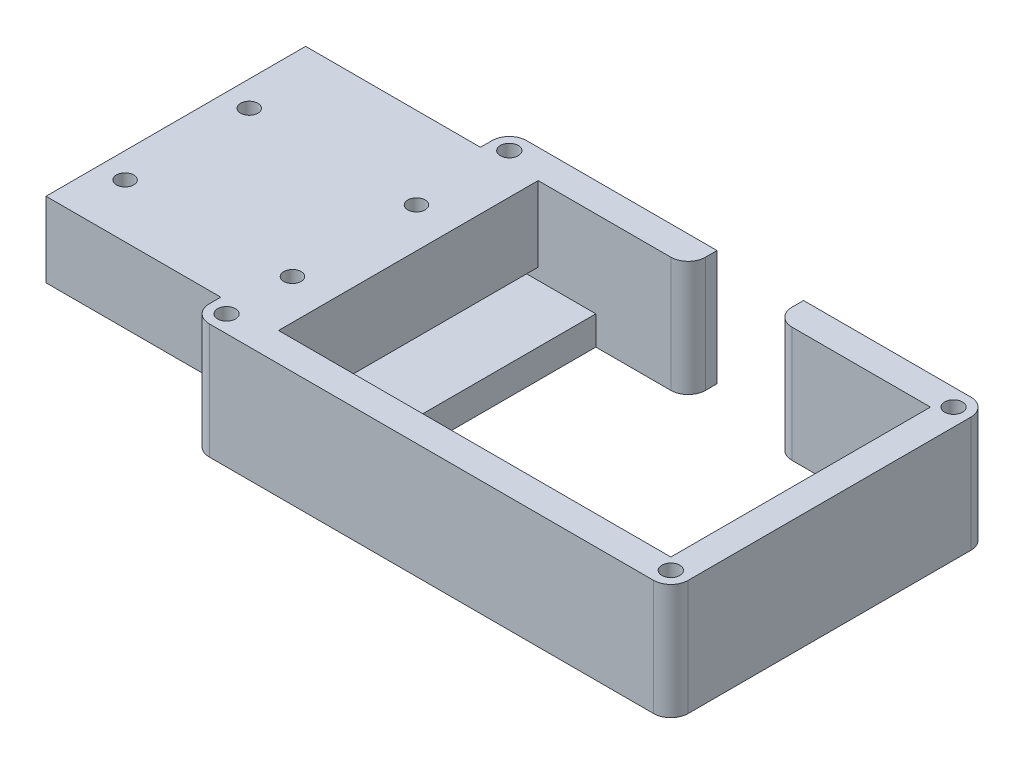
SolidWorks part; units mm, degrees
ref_plane "前视基准面" through (0, 0, 0) normal (0, 0, 1) x (1, 0, 0)
ref_plane "上视基准面" through (0, 0, 0) normal (0, 1, 0) x (1, 0, 0)
ref_plane "右视基准面" through (0, 0, 0) normal (1, 0, 0) x (0, 0, -1)
other "Configuration Table"
sketch "草图1" plane through (0, 0, 0) normal (0, 0, 1) x (1, 0, 0)
  line L0 (-1.15, 3.9875) -> (-1.15, 12)
  line L1 (0, 0) -> (0, 9.969) construction
  line L2 (-1.15, 12) -> (-4.15, 12)
  line L3 (-4.15, 12) -> (-4.15, 4.3333)
  line L4 (4.15, 12) -> (4.15, 4.3333)
  line L5 (1.15, 12) -> (4.15, 12)
  line L6 (1.15, 3.9875) -> (1.15, 12)
  line L7 (-8, -2.2655) -> (-5.2977, 2.8168)
  line L8 (-8, -2.2655) -> (-8, -30)
  line L9 (4.2426, -4.2426) -> (0, -8.4853)
  line L10 (0, -8.4853) -> (0, -30)
  line L11 (-8, -30) -> (0, -30)
  arc A0 (-1.15, 3.9875) -> (1.15, 3.9875) centre (0, 0) ccw
  arc A1 (-4.15, 4.3333) -> (-5.2977, 2.8168) centre (0, 0) ccw
  arc A2 (4.2426, -4.2426) -> (4.15, 4.3333) centre (0, 0) ccw
  dimension "D1" = 8.3
  dimension "D4" = 12
  dimension "D2" = 2.3
  dimension "D3" = 12
  dimension "D5" = 3
  dimension "D6" = 30
  dimension "D7" = 152
  dimension "D8" = 8
  dimension "D9" = 135
extrude "凸台-拉伸1" add sketch "草图1" along normal mid plane 20
sketch "草图2" plane through (0, 0, 0) normal (1, 0, 0) x (0, 0, -1)
  line L0 (-10, -30) -> (10, -30) construction
  circle A0 centre (0, -30) radius 10
extrude "凸台-拉伸2" add sketch "草图2" against normal up to surface and the other way blind 2 up to face at (-8, -16.1327, 0)
sketch "草图6" plane through (4.15, 0, 0) normal (1, 0, 0) x (0, 0, -1)
  line L0 (0, 0) -> (0, 16.5087) construction
  line L1 (-10, 12) -> (10, 12) construction
  line L2 (-5.5, 7.5) -> (-20.2045, 7.5)
  line L3 (-5.5, 7.5) -> (-5.5, 16.0204)
  line L4 (-5.5, 16.0204) -> (-20.2045, 16.0204)
  line L5 (-20.2045, 7.5) -> (-20.2045, 16.0204)
  line L6 (20.2045, 7.5) -> (20.2045, 16.0204)
  line L7 (5.5, 16.0204) -> (20.2045, 16.0204)
  line L8 (5.5, 7.5) -> (5.5, 16.0204)
  line L9 (5.5, 7.5) -> (20.2045, 7.5)
  circle A0 centre (0, 9.5) radius 1.65
  dimension "D3" = 3.3
  dimension "D1" = 11
  dimension "D2" = 4.5
  dimension "D4" = 2.5
extrude "切除-拉伸2" cut sketch "草图6" against normal through all
fillet "圆角1" radius 1 8 edges at (2.65, 7.5, -10) (-2.65, 7.5, -10) (-2.65, 7.5, 10) (2.65, 7.5, 10) (-2.65, 12, 5.5) (2.65, 12, -5.5) (-2.65, 12, -5.5) (2.65, 12, 5.5)
fillet "圆角2" radius 0.5 4 edges at (2.65, 7.5, -5.5) (-2.65, 7.5, -5.5) (2.65, 7.5, 5.5) (-2.65, 7.5, 5.5)
sketch "草图7" plane through (2, 0, 0) normal (1, 0, 0) x (0, 0, -1)
  line L0 (0, -20) -> (-22, -20)
  line L1 (0, -40) -> (-22, -40)
  line L2 (-22, -20) -> (-22, -40)
  arc A0 (0, -20) -> (0, -40) centre (0, -30) cw
  arc A1 (10, -30) -> (-10, -30) centre (0, -30) ccw construction
  dimension "D1" = 22
  dimension "D2" = 22
extrude "凸台-拉伸3" add sketch "草图7" along normal blind 8
sketch "草图8" plane through (0, 0, 22) normal (0, 0, 1) x (1, 0, 0)
  line L0 (2, -27) -> (2, -49.77) construction
  line L1 (10, -20) -> (-26, -20)
  line L2 (-26, -20) -> (-26, -40)
  line L3 (-26, -40) -> (2, -40)
  line L4 (10, -20) -> (57, -20)
  line L5 (2, -40) -> (57, -40)
  line L6 (57, -20) -> (57, -40)
  dimension "D1" = 36
  dimension "D2" = 20
  dimension "D3" = 47
extrude "凸台-拉伸4" add sketch "草图8" along normal blind 55
sketch "草图9" plane through (0, -20, 0) normal (0, 1, 0) x (1, 0, 0)
  line L0 (57, -22) -> (10, -22) construction
  line L1 (-21, -27) -> (52, -27)
  line L2 (-21, -27) -> (-21, -72)
  line L3 (-21, -72) -> (52, -72)
  line L4 (52, -27) -> (52, -72)
  line L5 (57, -77) -> (57, -22) construction
  line L6 (-26, -77) -> (-26, -22) construction
  line L7 (57, -77) -> (-26, -77) construction
  dimension "D1" = 5
  dimension "D2" = 5
  dimension "D3" = 5
  dimension "D4" = 5
extrude "切除-拉伸3" cut sketch "草图9" against normal blind 13
sketch "草图10" plane through (0, 0, 22) normal (0, 0, -1) x (-1, 0, 0)
  line L0 (-10, -40) -> (-57, -40) construction
  line L1 (-10, -20) -> (-25, -20)
  line L2 (-10, -20) -> (-10, -40)
  line L3 (-10, -40) -> (-25, -40)
  line L4 (-25, -20) -> (-25, -40)
  dimension "D1" = 15
extrude "切除-拉伸4" cut sketch "草图10" against normal blind 13
sketch "草图11" plane through (0, -33, 0) normal (0, 1, 0) x (1, 0, 0)
  line L1 (-21, -72) -> (52, -72)
  line L2 (-21, -72) -> (-21, -27)
  line L3 (-21, -27) -> (52, -27)
  line L4 (52, -72) -> (52, -27)
extrude "切除-拉伸6" cut sketch "草图11" against normal blind 13
sketch "草图12" plane through (0, -40, 0) normal (0, -1, 0) x (1, 0, 0)
  line L0 (-21, 72) -> (52, 72) construction
  line L1 (-21, 27) -> (-6, 27)
  line L2 (-21, 27) -> (-21, 72)
  line L3 (-21, 72) -> (-6, 72)
  line L4 (-6, 27) -> (-6, 72)
  line L6 (52, 27) -> (42, 27)
  line L7 (52, 27) -> (52, 72)
  line L8 (52, 72) -> (42, 72)
  line L9 (42, 27) -> (42, 72)
  dimension "D1" = 10
  dimension "D2" = 15
extrude "凸台-拉伸5" add sketch "草图12" against normal blind 5
fillet "圆角3" radius 3 5 edges at (-26, -30, 77) (-26, -30, 22) (57, -30, 22) (57, -30, 77) (25, -30, 27)
sketch "草图14" plane through (0, -20, 0) normal (0, 1, 0) x (1, 0, 0)
  circle A0 centre (-23, -25) radius 1.55
  circle A1 centre (54, -25) radius 1.55
  circle A2 centre (-23, -74) radius 1.55
  circle A3 centre (54, -74) radius 1.55
  dimension "D1" = 3.1
  dimension "D2" = 3.1
  dimension "D3" = 3.1
  dimension "D4" = 3.1
  dimension "D5" = 49
  dimension "D6" = 77
extrude "切除-拉伸7" cut sketch "草图14" against normal through all
sketch "草图15" plane through (0, -20, 0) normal (0, 1, 0) x (1, 0, 0)
  line L1 (2, -22) -> (10, -22)
  line L2 (2, -22) -> (2, 0)
  line L3 (2, 0) -> (10, 0)
  line L4 (10, -22) -> (10, 0)
extrude "切除-拉伸8" cut sketch "草图15" against normal blind 20
sketch "草图18" plane through (0, -20, 0) normal (0, 1, 0) x (1, 0, 0)
  line L0 (-21, -72) -> (52, -72) construction
  line L1 (-21, -27) -> (-56.3, -27)
  line L2 (-21, -27) -> (-21, -72)
  line L3 (-21, -72) -> (-56.3, -72)
  line L4 (-56.3, -27) -> (-56.3, -72)
  line L5 (-21, -27) -> (-16, -27)
  line L6 (-21, -27) -> (-21, -72)
  line L7 (-21, -72) -> (-16, -72)
  line L8 (-16, -27) -> (-16, -72)
  line M16 (-26, -25) -> (-26, -74)
  line M27 (52, -72) -> (-21, -72)
  line M28 (-21, -72) -> (-21, -27)
  line M29 (-21, -27) -> (7, -27)
  dimension "D1" = 5
  dimension "D2" = 35.3
extrude "凸台-拉伸6" add sketch "草图18" against normal blind 13 contours L8 M29 M28 M27 | L1 L4 L3 M16
sketch "草图20" plane through (0, -20, 0) normal (0, 1, 0) x (1, 0, 0)
  circle A2 centre (-22.8953, -62.695) radius 1.5
  circle A3 centre (-51.8953, -41.1795) radius 1.5
  circle A4 centre (-21.9492, 0) radius 1.5
  circle A5 centre (-51.8953, -62.695) radius 1.5
  circle A6 centre (-22.8953, -41.195) radius 1.5
  point P0 (-51.8953, -62.695)
  point P10 (-45.3901, -31)
  point P11 (-19.757, -64.1776)
  point P14 (-45.3901, -62.5925)
  point P15 (0, 0)
  point P16 (0, 0)
  point P17 (0, 0)
  point P18 (0, 0)
  point P19 (0, 0)
  point P20 (-44.4581, -59.4304)
  point P21 (-44.3698, -53.7011)
  point P22 (-44.3698, -41.193)
  point P23 (-23, -31)
  point P26 (-25.7119, -39.4364)
  point P27 (0, 0)
  point P28 (-26.7571, -41.193)
  point P29 (-26.7571, -53.1463)
  point P30 (0, 0)
  point P31 (-44.3698, -53.1463)
  dimension "D1" = 29
  dimension "D2" = 21.5
extrude "切除-拉伸9" cut sketch "草图20" against normal blind 13
